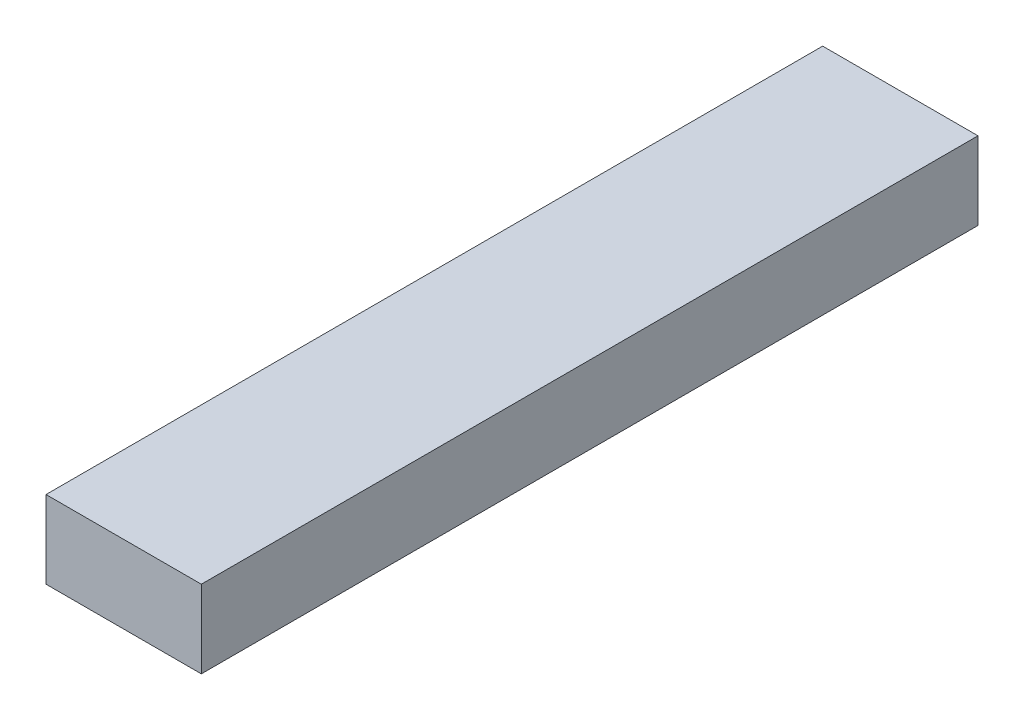
SolidWorks part; units mm, degrees
ref_plane "Front Plane" through (0, 0, 0) normal (0, 0, 1) x (1, 0, 0)
ref_plane "Top Plane" through (0, 0, 0) normal (0, 1, 0) x (1, 0, 0)
ref_plane "Right Plane" through (0, 0, 0) normal (1, 0, 0) x (0, 0, -1)
sketch "Sketch1" plane through (0, 0, 0) normal (0, 0, 1) x (1, 0, 0)
  line L1 (0, 0) -> (40, 0)
  line L2 (0, 0) -> (0, 20)
  line L3 (0, 20) -> (40, 20)
  line L4 (40, 0) -> (40, 20)
  dimension "D1" = 40
  dimension "D2" = 20
extrude "Boss-Extrude1" add sketch "Sketch1" along normal blind 200
